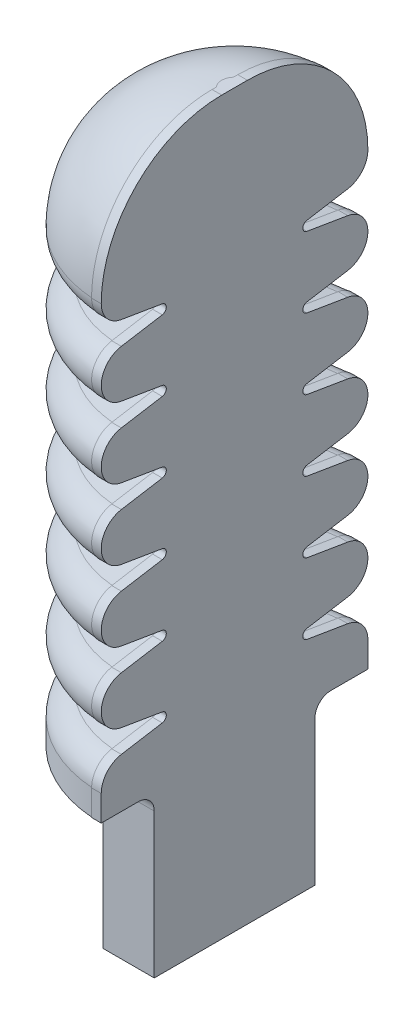
SolidWorks part; units mm, degrees
ref_plane "Front Plane" through (0, 0, 0) normal (0, 0, 1) x (1, 0, 0)
ref_plane "Top Plane" through (0, 0, 0) normal (0, 1, 0) x (1, 0, 0)
ref_plane "Right Plane" through (0, 0, 0) normal (1, 0, 0) x (0, 0, -1)
sketch "Sketch1" plane through (0, 0, 0) normal (1, 0, 0) x (0, 0, -1)
  line L0 (-9.6168, 62.5511) -> (-3.2517, 61.4898)
  line L3 (6, 85) -> (8, 85)
  line L4 (8, 83) -> (8, 85)
  line L5 (-10.7758, 0.25) -> (-12.75, 0.25)
  line L6 (-9.6168, 58.949) -> (-3.2517, 60.0102)
  line L7 (-2.9428, 52.4658) -> (-9.2826, 53.4748)
  line L9 (6, 83) -> (8, 83)
  line L10 (8, 83) -> (8, 85)
  line L11 (8, 83) -> (8, 0) construction
  line L13 (-9.6168, 40.5511) -> (-3.2517, 39.4898)
  line L14 (-9.6168, 51.5511) -> (-3.2517, 50.4898)
  line L15 (-9.6167, 47.949) -> (-3.2517, 49.0102)
  line L16 (-9.6167, 36.949) -> (-3.2517, 38.0102)
  line L17 (-9.6168, 29.5511) -> (-3.2517, 28.4898)
  line L18 (-9.6168, 18.5511) -> (-3.2517, 17.4898)
  line L19 (-9.6167, 14.949) -> (-3.2517, 16.0102)
  line L20 (-9.6168, 7.5511) -> (-3.2517, 6.4898)
  line L21 (-9.6168, 3.949) -> (-3.2517, 5.0102)
  line L22 (-9.2878, 64.5239) -> (-2.9227, 63.4626)
  line L23 (-9.2676, 46.086) -> (-2.9674, 47.0304)
  line L24 (-9.2678, 42.4141) -> (-2.9227, 41.4626)
  line L25 (-9.2826, 35.0031) -> (-2.9336, 36.0357)
  line L26 (-9.2826, 31.4969) -> (-2.9336, 30.4643)
  line L27 (-9.6167, 25.949) -> (-3.2517, 27.0102)
  line L28 (-9.2826, 24.0031) -> (-2.9336, 25.0357)
  line L29 (-9.2826, 20.4969) -> (-2.9336, 19.4643)
  line L30 (-9.2826, 13.0031) -> (-2.9336, 14.0357)
  line L31 (-9.2826, 9.4969) -> (-2.9336, 8.4643)
  line L32 (-9.2825, 2.0031) -> (-2.9336, 3.0357)
  line L33 (-9.2825, 57.0252) -> (-2.9428, 58.0342)
  arc A0 (6, 85) -> (-12.75, 66.25) centre (6, 66.25) ccw
  arc A2 (-12.75, 66.25) -> (-9.6168, 62.5511) centre (-9, 66.25) ccw
  arc A4 (-9.6167, 47.949) -> (-9.6168, 40.5511) centre (-9, 44.25) ccw
  arc A5 (-9.6167, 36.949) -> (-9.6168, 29.5511) centre (-9, 33.25) ccw
  arc A6 (-9.6167, 25.949) -> (-9.6168, 18.5511) centre (-9, 22.25) ccw
  arc A7 (-9.6167, 14.949) -> (-9.6168, 7.5511) centre (-9, 11.25) ccw
  arc A8 (-2.9428, 58.0342) -> (-2.9227, 63.4626) centre (-3.375, 60.75) ccw
  arc A9 (-2.9674, 47.0304) -> (-2.9428, 52.4658) centre (-3.375, 49.75) ccw
  arc A10 (-2.9336, 36.0357) -> (-2.9227, 41.4626) centre (-3.375, 38.75) ccw
  arc A11 (-2.9336, 25.0357) -> (-2.9336, 30.4643) centre (-3.375, 27.75) ccw
  arc A12 (-2.9336, 14.0357) -> (-2.9336, 19.4643) centre (-3.375, 16.75) ccw
  arc A14 (-9.6167, 3.949) -> (-12.75, 0.25) centre (-9, 0.25) ccw
  arc A15 (-2.9336, 3.0357) -> (-2.9336, 8.4643) centre (-3.375, 5.75) ccw
  arc A16 (-10.75, 66.25) -> (-9.2878, 64.5239) centre (-9, 66.25) ccw
  arc A17 (-3.2517, 60.0102) -> (-3.2517, 61.4898) centre (-3.375, 60.75) ccw
  arc A18 (-9.2825, 57.0252) -> (-9.2826, 53.4748) centre (-9, 55.25) ccw
  arc A19 (-3.2517, 49.0102) -> (-3.2517, 50.4898) centre (-3.375, 49.75) ccw
  arc A20 (-9.2676, 46.086) -> (-9.2678, 42.4141) centre (-9, 44.25) ccw
  arc A21 (-3.2517, 38.0102) -> (-3.2517, 39.4898) centre (-3.375, 38.75) ccw
  arc A22 (-9.2826, 35.0031) -> (-9.2826, 31.4969) centre (-9, 33.25) ccw
  arc A23 (-3.2517, 27.0102) -> (-3.2517, 28.4898) centre (-3.375, 27.75) ccw
  arc A24 (-9.2826, 24.0031) -> (-9.2826, 20.4969) centre (-9, 22.25) ccw
  arc A25 (-3.2517, 16.0102) -> (-3.2517, 17.4898) centre (-3.375, 16.75) ccw
  arc A26 (-9.2826, 13.0031) -> (-9.2826, 9.4969) centre (-9, 11.25) ccw
  arc A27 (-3.2517, 5.0102) -> (-3.2517, 6.4898) centre (-3.375, 5.75) ccw
  arc A28 (-9.2825, 2.0031) -> (-10.7758, 0.25) centre (-9, 0.25) ccw
  arc A29 (6, 83) -> (-10.75, 66.25) centre (6, 66.25) ccw
  arc A32 (-9.6167, 58.949) -> (-9.6168, 51.5511) centre (-9, 55.25) ccw
  dimension "D4" = 18.75
  dimension "D6" = 7.5
  dimension "D11" = 11
  dimension "D13" = 5.5
  dimension "D21" = 2
  dimension "D22" = 2
  dimension "D7" = 11
  dimension "D8" = 11
  dimension "D9" = 11
  dimension "D10" = 11
  dimension "D12" = 11
  dimension "D15" = 11
  dimension "D16" = 11
  dimension "D17" = 11
  dimension "D18" = 11
  dimension "D19" = 11
revolve "Revolve2" add sketch "Sketch1" angle 180 about L11
sketch "Sketch2" plane through (0, 0.25, 0) normal (0, -1, 0) x (1, 0, 0)
  line L0 (0, 12.75) -> (0, -28.75)
  arc A0 (0, 12.75) -> (0, -28.75) centre (0, -8) ccw
  circle A1 centre (-4, -8) radius 2.05
  dimension "D1" = 4.1
  dimension "D2" = 4
extrude "Boss-Extrude1" add sketch "Sketch2" along normal blind 4
sketch "Sketch3" plane through (0, 0, 0) normal (1, 0, 0) x (0, 0, -1)
  line L84 (-12.75, 0.25) -> (-12.75, -3.75)
  line L85 (-12.75, -3.75) -> (28.75, -3.75)
  line L86 (28.75, -3.75) -> (28.75, 0.25)
  line L87 (25.6168, 3.949) -> (19.2517, 5.0102)
  line L88 (19.2517, 6.4898) -> (25.6168, 7.5511)
  line L89 (25.6167, 14.949) -> (19.2517, 16.0102)
  line L90 (19.2517, 17.4898) -> (25.6168, 18.5511)
  line L91 (25.6167, 25.949) -> (19.2517, 27.0102)
  line L92 (19.2517, 28.4898) -> (25.6168, 29.5511)
  line L93 (25.6167, 36.949) -> (19.2517, 38.0102)
  line L94 (19.2517, 39.4898) -> (25.6168, 40.5511)
  line L95 (25.6167, 47.949) -> (19.2517, 49.0102)
  line L96 (19.2517, 50.4898) -> (25.6168, 51.5511)
  line L97 (25.6168, 58.949) -> (19.2517, 60.0102)
  line L98 (19.2517, 61.4898) -> (25.6168, 62.5511)
  line L99 (10, 85) -> (6, 85)
  line L100 (-9.6168, 62.5511) -> (-3.2517, 61.4898)
  line L101 (-3.2517, 60.0102) -> (-9.6168, 58.949)
  line L102 (-9.6168, 51.5511) -> (-3.2517, 50.4898)
  line L103 (-3.2517, 49.0102) -> (-9.6167, 47.949)
  line L104 (-9.6168, 40.5511) -> (-3.2517, 39.4898)
  line L105 (-3.2517, 38.0102) -> (-9.6167, 36.949)
  line L106 (-9.6168, 29.5511) -> (-3.2517, 28.4898)
  line L107 (-3.2517, 27.0102) -> (-9.6167, 25.949)
  line L108 (-9.6168, 18.5511) -> (-3.2517, 17.4898)
  line L109 (-3.2517, 16.0102) -> (-9.6167, 14.949)
  line L110 (-9.6168, 7.5511) -> (-3.2517, 6.4898)
  line L111 (-3.2517, 5.0102) -> (-9.6168, 3.949)
  line L112 (-12.75, 0.25) -> (-12.75, -3.75)
  line L113 (-12.75, -3.75) -> (28.75, -3.75)
  line L114 (28.75, -3.75) -> (28.75, 0.25)
  line L115 (25.6168, 3.949) -> (19.2517, 5.0102)
  line L116 (19.2517, 6.4898) -> (25.6168, 7.5511)
  line L117 (25.6167, 14.949) -> (19.2517, 16.0102)
  line L118 (19.2517, 17.4898) -> (25.6168, 18.5511)
  line L119 (25.6167, 25.949) -> (19.2517, 27.0102)
  line L120 (19.2517, 28.4898) -> (25.6168, 29.5511)
  line L121 (25.6167, 36.949) -> (19.2517, 38.0102)
  line L122 (19.2517, 39.4898) -> (25.6168, 40.5511)
  line L123 (25.6167, 47.949) -> (19.2517, 49.0102)
  line L124 (19.2517, 50.4898) -> (25.6168, 51.5511)
  line L125 (25.6168, 58.949) -> (19.2517, 60.0102)
  line L126 (19.2517, 61.4898) -> (25.6168, 62.5511)
  line L127 (10, 85) -> (6, 85)
  line L128 (-9.6168, 62.5511) -> (-3.2517, 61.4898)
  line L129 (-3.2517, 60.0102) -> (-9.6168, 58.949)
  line L130 (-9.6168, 51.5511) -> (-3.2517, 50.4898)
  line L131 (-3.2517, 49.0102) -> (-9.6167, 47.949)
  line L132 (-9.6168, 40.5511) -> (-3.2517, 39.4898)
  line L133 (-3.2517, 38.0102) -> (-9.6167, 36.949)
  line L134 (-9.6168, 29.5511) -> (-3.2517, 28.4898)
  line L135 (-3.2517, 27.0102) -> (-9.6167, 25.949)
  line L136 (-9.6168, 18.5511) -> (-3.2517, 17.4898)
  line L137 (-3.2517, 16.0102) -> (-9.6167, 14.949)
  line L138 (-9.6168, 7.5511) -> (-3.2517, 6.4898)
  line L139 (-3.2517, 5.0102) -> (-9.6168, 3.949)
  arc A84 (-9.6168, 3.949) -> (-12.75, 0.25) centre (-9, 0.25) ccw
  arc A85 (28.75, 0.25) -> (25.6168, 3.949) centre (25, 0.25) ccw
  arc A86 (19.2517, 6.4898) -> (19.2517, 5.0102) centre (19.375, 5.75) ccw
  arc A87 (25.6168, 7.5511) -> (25.6167, 14.949) centre (25, 11.25) ccw
  arc A88 (19.2517, 17.4898) -> (19.2517, 16.0102) centre (19.375, 16.75) ccw
  arc A89 (25.6168, 18.5511) -> (25.6167, 25.949) centre (25, 22.25) ccw
  arc A90 (19.2517, 28.4898) -> (19.2517, 27.0102) centre (19.375, 27.75) ccw
  arc A91 (25.6168, 29.5511) -> (25.6167, 36.949) centre (25, 33.25) ccw
  arc A92 (19.2517, 39.4898) -> (19.2517, 38.0102) centre (19.375, 38.75) ccw
  arc A93 (25.6168, 40.5511) -> (25.6167, 47.949) centre (25, 44.25) ccw
  arc A94 (19.2517, 50.4898) -> (19.2517, 49.0102) centre (19.375, 49.75) ccw
  arc A95 (25.6168, 51.5511) -> (25.6168, 58.949) centre (25, 55.25) ccw
  arc A96 (19.2517, 61.4898) -> (19.2517, 60.0102) centre (19.375, 60.75) ccw
  arc A97 (25.6168, 62.5511) -> (28.75, 66.25) centre (25, 66.25) ccw
  arc A98 (28.75, 66.25) -> (10, 85) centre (10, 66.25) ccw
  arc A99 (6, 85) -> (-12.75, 66.25) centre (6, 66.25) ccw
  arc A100 (-12.75, 66.25) -> (-9.6168, 62.5511) centre (-9, 66.25) ccw
  arc A101 (-3.2517, 60.0102) -> (-3.2517, 61.4898) centre (-3.375, 60.75) ccw
  arc A102 (-9.6168, 58.949) -> (-9.6168, 51.5511) centre (-9, 55.25) ccw
  arc A103 (-3.2517, 49.0102) -> (-3.2517, 50.4898) centre (-3.375, 49.75) ccw
  arc A104 (-9.6167, 47.949) -> (-9.6168, 40.5511) centre (-9, 44.25) ccw
  arc A105 (-3.2517, 38.0102) -> (-3.2517, 39.4898) centre (-3.375, 38.75) ccw
  arc A106 (-9.6167, 36.949) -> (-9.6168, 29.5511) centre (-9, 33.25) ccw
  arc A107 (-3.2517, 27.0102) -> (-3.2517, 28.4898) centre (-3.375, 27.75) ccw
  arc A108 (-9.6167, 25.949) -> (-9.6168, 18.5511) centre (-9, 22.25) ccw
  arc A109 (-3.2517, 16.0102) -> (-3.2517, 17.4898) centre (-3.375, 16.75) ccw
  arc A110 (-9.6167, 14.949) -> (-9.6168, 7.5511) centre (-9, 11.25) ccw
  arc A111 (-3.2517, 5.0102) -> (-3.2517, 6.4898) centre (-3.375, 5.75) ccw
  arc A112 (-9.6168, 3.949) -> (-12.75, 0.25) centre (-9, 0.25) ccw
  arc A113 (28.75, 0.25) -> (25.6168, 3.949) centre (25, 0.25) ccw
  arc A114 (19.2517, 6.4898) -> (19.2517, 5.0102) centre (19.375, 5.75) ccw
  arc A115 (25.6168, 7.5511) -> (25.6167, 14.949) centre (25, 11.25) ccw
  arc A116 (19.2517, 17.4898) -> (19.2517, 16.0102) centre (19.375, 16.75) ccw
  arc A117 (25.6168, 18.5511) -> (25.6167, 25.949) centre (25, 22.25) ccw
  arc A118 (19.2517, 28.4898) -> (19.2517, 27.0102) centre (19.375, 27.75) ccw
  arc A119 (25.6168, 29.5511) -> (25.6167, 36.949) centre (25, 33.25) ccw
  arc A120 (19.2517, 39.4898) -> (19.2517, 38.0102) centre (19.375, 38.75) ccw
  arc A121 (25.6168, 40.5511) -> (25.6167, 47.949) centre (25, 44.25) ccw
  arc A122 (19.2517, 50.4898) -> (19.2517, 49.0102) centre (19.375, 49.75) ccw
  arc A123 (25.6168, 51.5511) -> (25.6168, 58.949) centre (25, 55.25) ccw
  arc A124 (19.2517, 61.4898) -> (19.2517, 60.0102) centre (19.375, 60.75) ccw
  arc A125 (25.6168, 62.5511) -> (28.75, 66.25) centre (25, 66.25) ccw
  arc A126 (28.75, 66.25) -> (10, 85) centre (10, 66.25) ccw
  arc A127 (6, 85) -> (-12.75, 66.25) centre (6, 66.25) ccw
  arc A128 (-12.75, 66.25) -> (-9.6168, 62.5511) centre (-9, 66.25) ccw
  arc A129 (-3.2517, 60.0102) -> (-3.2517, 61.4898) centre (-3.375, 60.75) ccw
  arc A130 (-9.6168, 58.949) -> (-9.6168, 51.5511) centre (-9, 55.25) ccw
  arc A131 (-3.2517, 49.0102) -> (-3.2517, 50.4898) centre (-3.375, 49.75) ccw
  arc A132 (-9.6167, 47.949) -> (-9.6168, 40.5511) centre (-9, 44.25) ccw
  arc A133 (-3.2517, 38.0102) -> (-3.2517, 39.4898) centre (-3.375, 38.75) ccw
  arc A134 (-9.6167, 36.949) -> (-9.6168, 29.5511) centre (-9, 33.25) ccw
  arc A135 (-3.2517, 27.0102) -> (-3.2517, 28.4898) centre (-3.375, 27.75) ccw
  arc A136 (-9.6167, 25.949) -> (-9.6168, 18.5511) centre (-9, 22.25) ccw
  arc A137 (-3.2517, 16.0102) -> (-3.2517, 17.4898) centre (-3.375, 16.75) ccw
  arc A138 (-9.6167, 14.949) -> (-9.6168, 7.5511) centre (-9, 11.25) ccw
  arc A139 (-3.2517, 5.0102) -> (-3.2517, 6.4898) centre (-3.375, 5.75) ccw
  dimension "D1" = 0
extrude "Boss-Extrude2" add sketch "Sketch3" against normal blind 1.5
sketch "Sketch4" plane through (0, -3.75, 0) normal (0, -1, 0) x (1, 0, 0)
  line L0 (0, -28.75) -> (0, 12.75) construction
  line L1 (-8, -20.5) -> (0, -20.5)
  line L2 (-8, -20.5) -> (-8, 4.5)
  line L3 (-8, 4.5) -> (0, 4.5)
  line L4 (0, -20.5) -> (0, 4.5)
  line L5 (-8, -20.5) -> (0, 4.5) construction
  line L6 (-8, 4.5) -> (0, -20.5) construction
  circle A0 centre (-4, -8) radius 2.05
  point P0 (-4, -8)
  dimension "D1" = 25
extrude "Boss-Extrude3" add sketch "Sketch4" along normal blind 25
fillet "Fillet1" radius 2.5 2 edges at (-4, -3.75, -20.5) (-4, -3.75, 4.5)
sketch "Sketch5" plane through (-8, 0, 0) normal (-1, 0, 0) x (0, 0, 1)
  line L0 (7, -3.75) -> (-23, -3.75) construction
  line L1 (-14.495, -3.75) -> (-13.005, -3.75)
  line L2 (-14.495, -3.75) -> (-14.495, -13.75)
  line L3 (-14.495, -13.75) -> (-13.005, -13.75)
  line L4 (-13.005, -3.75) -> (-13.005, -13.75)
  line L5 (4.5, -28.75) -> (-20.5, -28.75) construction
  line L6 (-2.995, -3.75) -> (-1.505, -3.75)
  line L7 (-2.995, -3.75) -> (-2.995, -13.75)
  line L8 (-2.995, -13.75) -> (-1.505, -13.75)
  line L9 (-1.505, -3.75) -> (-1.505, -13.75)
  point P12 (-8, -28.75)
  dimension "D1" = 10.01
  dimension "D2" = 1.49
  dimension "D3" = 1.49
  dimension "D4" = 5.005
  dimension "D5" = 10
  dimension "D6" = 10
extrude "Boss-Extrude4" add sketch "Sketch5" along normal blind 1
